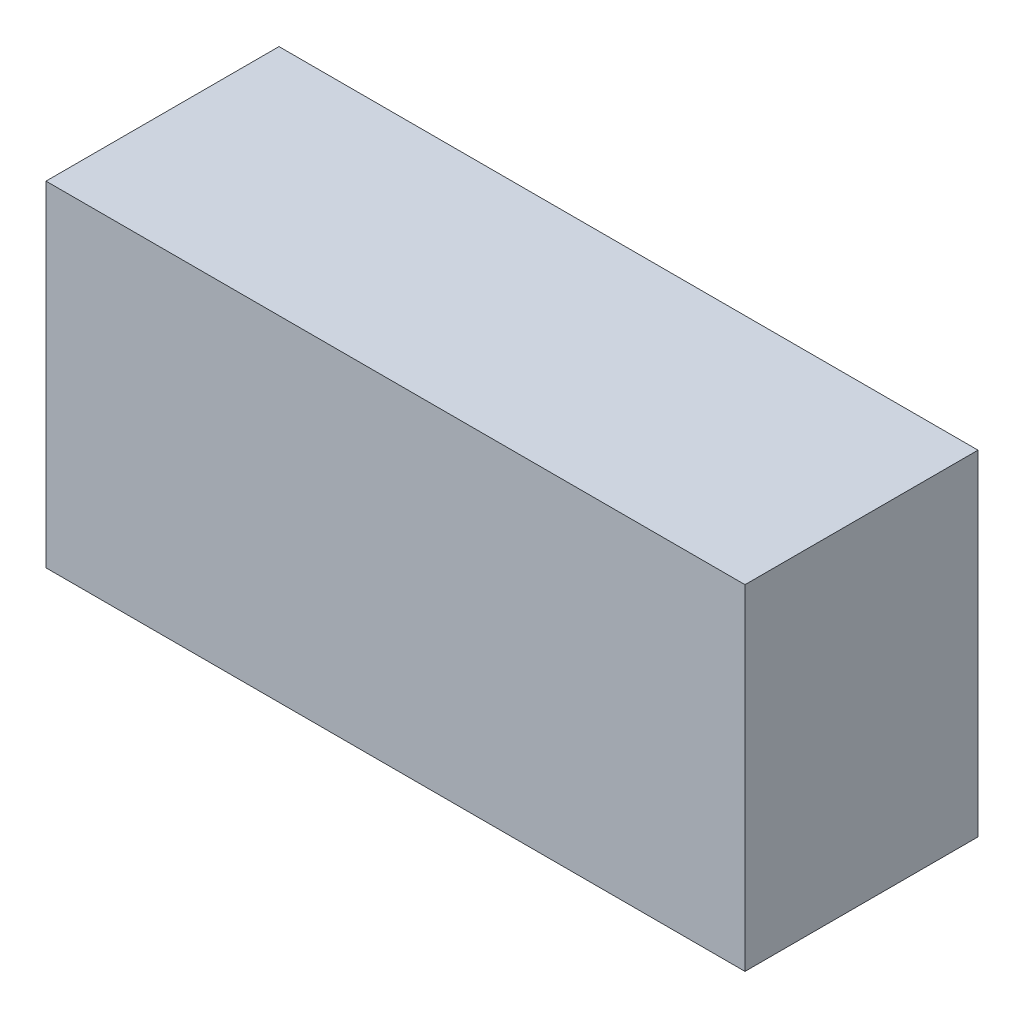
SolidWorks part; units mm, degrees
ref_plane "정면" through (0, 0, 0) normal (0, 0, 1) x (1, 0, 0)
ref_plane "윗면" through (0, 0, 0) normal (0, 1, 0) x (1, 0, 0)
ref_plane "우측면" through (0, 0, 0) normal (1, 0, 0) x (0, 0, -1)
sketch "스케치1" plane through (0, 0, 0) normal (0, 0, 1) x (1, 0, 0)
  line L1 (-240, 115) -> (240, 115)
  line L2 (-240, 115) -> (-240, -115)
  line L3 (-240, -115) -> (240, -115)
  line L4 (240, 115) -> (240, -115)
  line L5 (-240, 115) -> (240, -115) construction
  line L6 (-240, -115) -> (240, 115) construction
  point P0 (0, 0)
  dimension "D1" = 480
  dimension "D2" = 230
extrude "보스-돌출1" add sketch "스케치1" along normal blind 160
ref_plane "평면1" through (0, -115, 0) normal (0, -1, 0) x (-1, 0, 0)
sketch "스케치3" plane through (0, -115, 0) normal (0, -1, 0) x (-1, 0, 0)
  text T0 "OMOROBOT" font "Century Gothic" height 20
extrude "컷-돌출1" cut sketch "스케치3" against normal blind 5
sketch "스케치4" plane through (-240, 0, 0) normal (-1, 0, 0) x (0, 0, 1)
  line L0 (160, -115) -> (0, -115) construction
  line L1 (160, 115) -> (160, -115) construction
  point P0 (126, -50)
  dimension "D1" = 65
  dimension "D2" = 34
sketch "스케치5" plane through (240, 0, 0) normal (1, 0, 0) x (0, 0, -1)
  line L4 (0, -115) -> (0, 115)
  line L5 (0, 115) -> (-160, 115)
  line L6 (-160, 115) -> (-160, -115)
  line L7 (-160, -115) -> (0, -115)
  line L8 (0, -115) -> (0, 115)
  line L9 (0, 115) -> (-160, 115)
  line L10 (-160, 115) -> (-160, -115)
  line L11 (-160, -115) -> (0, -115)
  point P2 (-126, -50)
  dimension "D1" = 0
